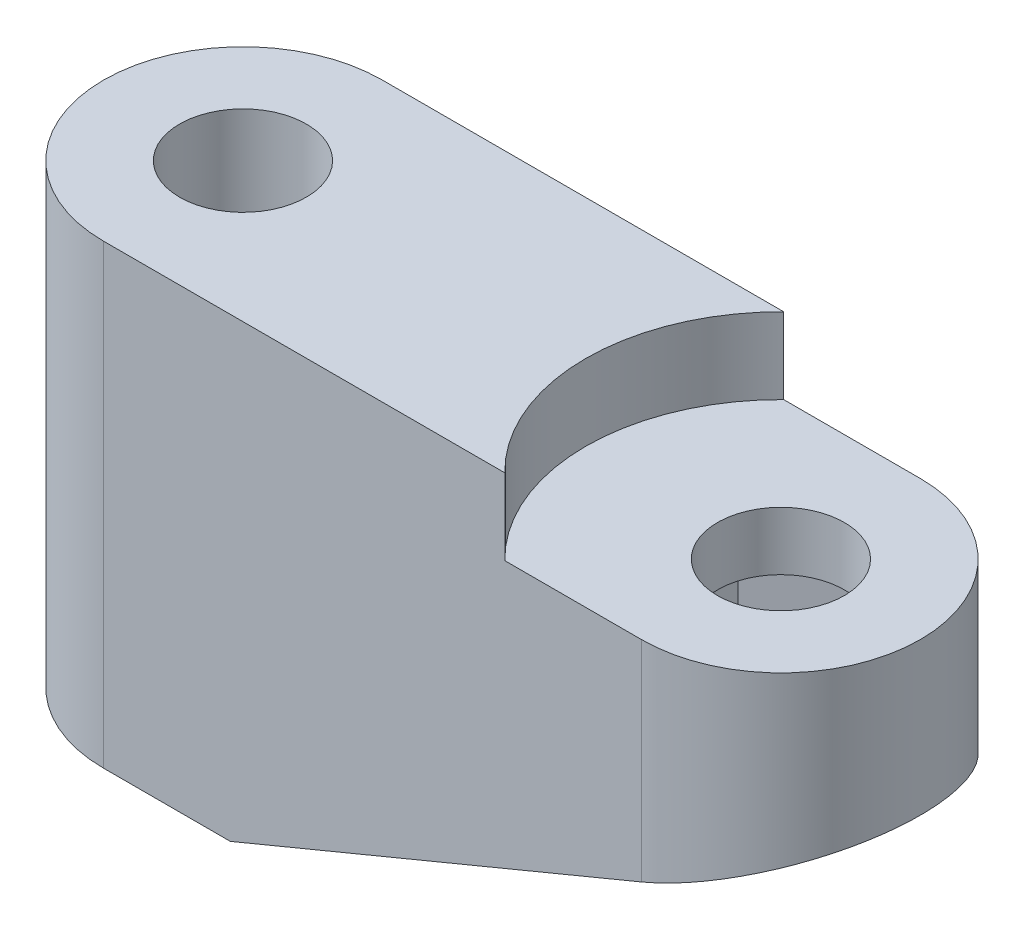
SolidWorks part; units mm, degrees
ref_plane "Alzado" through (0, 0, 0) normal (0, 0, 1) x (1, 0, 0)
ref_plane "Planta" through (0, 0, 0) normal (0, 1, 0) x (1, 0, 0)
ref_plane "Vista lateral" through (0, 0, 0) normal (1, 0, 0) x (0, 0, -1)
sketch "Croquis1" plane through (0, 0, 0) normal (0, 1, 0) x (1, 0, 0)
  line L0 (0, 0) -> (21.215, 0) construction
  line L1 (0, 5.5) -> (21.215, 5.5)
  line L2 (0, -5.5) -> (21.215, -5.5)
  circle A0 centre (0, 0) radius 2.5
  arc A1 (0, 5.5) -> (0, -5.5) centre (0, 0) ccw
  arc A2 (21.215, -5.5) -> (21.215, 5.5) centre (21.215, 0) ccw
  circle A3 centre (21.215, 0) radius 2.5
  dimension "D1" = 5
  dimension "D2" = 3
  dimension "D3" = 21.215
extrude "Saliente-Extruir1" add sketch "Croquis1" along normal blind 15
sketch "Croquis2" plane through (0, 0, 5.5) normal (0, 0, 1) x (1, 0, 0)
  line L0 (5, 15) -> (5, 0) construction
  line L1 (0, 15) -> (21.215, 15) construction
  line L2 (0, 0) -> (21.215, 0) construction
  line L3 (5, 7.5) -> (2.5, 7.5) construction
  line L4 (2.5, 0) -> (2.5, 15) construction
  line L5 (2.5, 7.5) -> (0, 7.5) construction
  line L6 (0, 15) -> (0, 0) construction
  line L7 (5, 0) -> (26.715, 9)
  line L8 (26.715, 0) -> (26.715, 15) construction
  line L9 (26.715, 9) -> (26.715, 0)
  line L10 (26.715, 0) -> (5, 0)
  dimension "D1" = 6
extrude "Cortar-Extruir1" cut sketch "Croquis2" against normal blind 15
ref_plane "Plano1" through (0, 9, 0) normal (0, 1, 0) x (1, 0, 0)
sketch "Croquis3" plane through (0, 9, 0) normal (0, 1, 0) x (1, 0, 0)
  line L1 (17.215, 2.3094) -> (17.215, -2.3094)
  line L2 (17.215, -2.3094) -> (21.215, -4.6188)
  line L3 (21.215, -4.6188) -> (25.215, -2.3094)
  line L4 (25.215, -2.3094) -> (25.215, 2.3094)
  line L5 (25.215, 2.3094) -> (21.215, 4.6188)
  line L6 (21.215, 4.6188) -> (17.215, 2.3094)
  circle A0 centre (21.215, 0) radius 4 construction
  dimension "D1" = 8
extrude "Cortar-Extruir2" cut sketch "Croquis3" against normal blind 15 and the other way blind 3.7
sketch "Croquis4" plane through (0, 15, 0) normal (0, 1, 0) x (1, 0, 0)
  line L2 (0, -5.5) -> (21.215, -5.5)
  line L3 (21.215, 5.5) -> (0, 5.5)
  line L4 (0, -5.5) -> (15.8261, -5.5)
  line L5 (15.8261, 5.5) -> (0, 5.5)
  circle A0 centre (0, 0) radius 2.5 construction
  circle A1 centre (0, 0) radius 2.5
  arc A2 (0, 5.5) -> (0, -5.5) centre (0, 0) ccw
  arc A3 (21.215, -5.5) -> (21.215, 5.5) centre (21.215, 0) ccw
  arc A4 (0, 5.5) -> (0, -5.5) centre (0, 0) ccw
  arc A6 (15.8261, 5.5) -> (15.8261, -5.5) centre (21.215, 0) ccw
  circle A7 centre (21.215, 0) radius 2.5 construction
  dimension "D2" = 5.2
  dimension "D1" = 0
extrude "Saliente-Extruir2" add sketch "Croquis4" along normal blind 3
